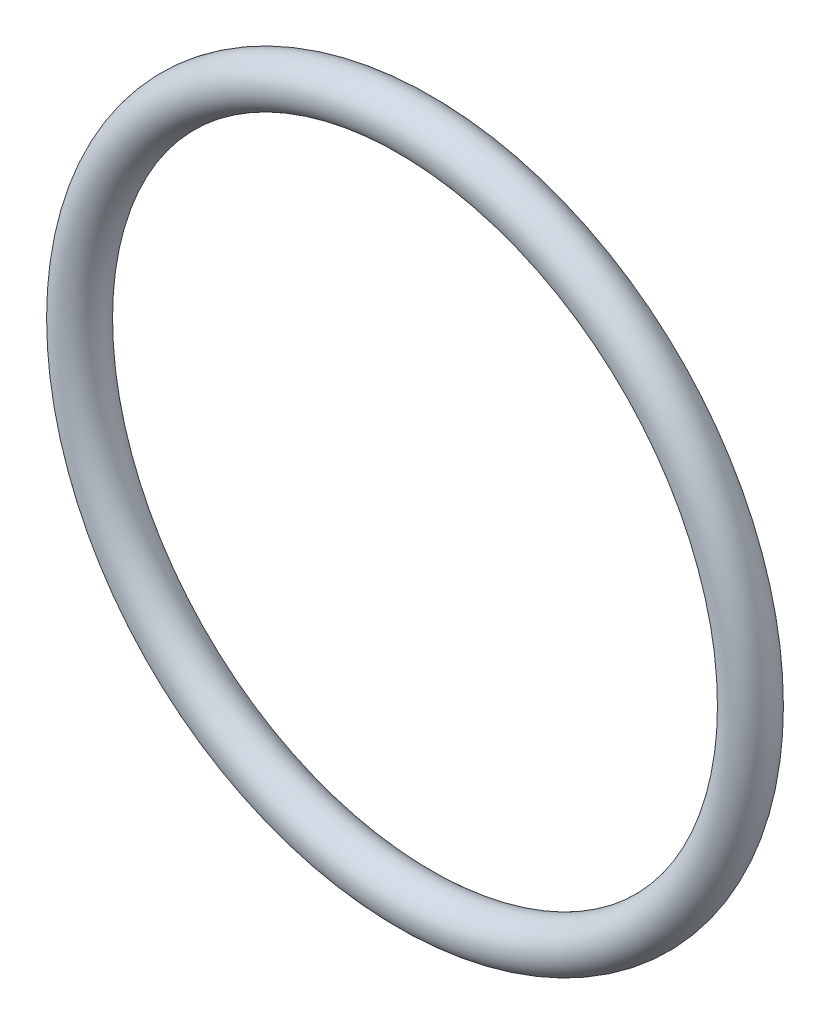
SolidWorks part; units mm, degrees
ref_plane "Front" through (0, 0, 0) normal (0, 0, 1) x (1, 0, 0)
ref_plane "Top" through (0, 0, 0) normal (0, 1, 0) x (1, 0, 0)
ref_plane "Right" through (0, 0, 0) normal (1, 0, 0) x (0, 0, -1)
sketch "Sketch1" plane through (0, 0, 0) normal (1, 0, 0) x (0, -1, 0)
  line L0 (0, -1.7653) -> (0, 1.7653) construction
  line L2 (-29.8539, 0) -> (29.8539, 0) construction
  line L3 (-23.6093, 0) -> (23.6093, 0) construction
  circle A0 centre (25.3746, 0) radius 1.7653
  point P9 (23.6093, 0)
  point P10 (27.1399, 0)
  point P13 (25.3746, 1.7653)
  point P14 (25.3746, -1.7653)
  dimension "Width" = 3.5306
  dimension "ID" = 47.2186
revolve "Revolve1" add sketch "Sketch1" angle 360 about L0
